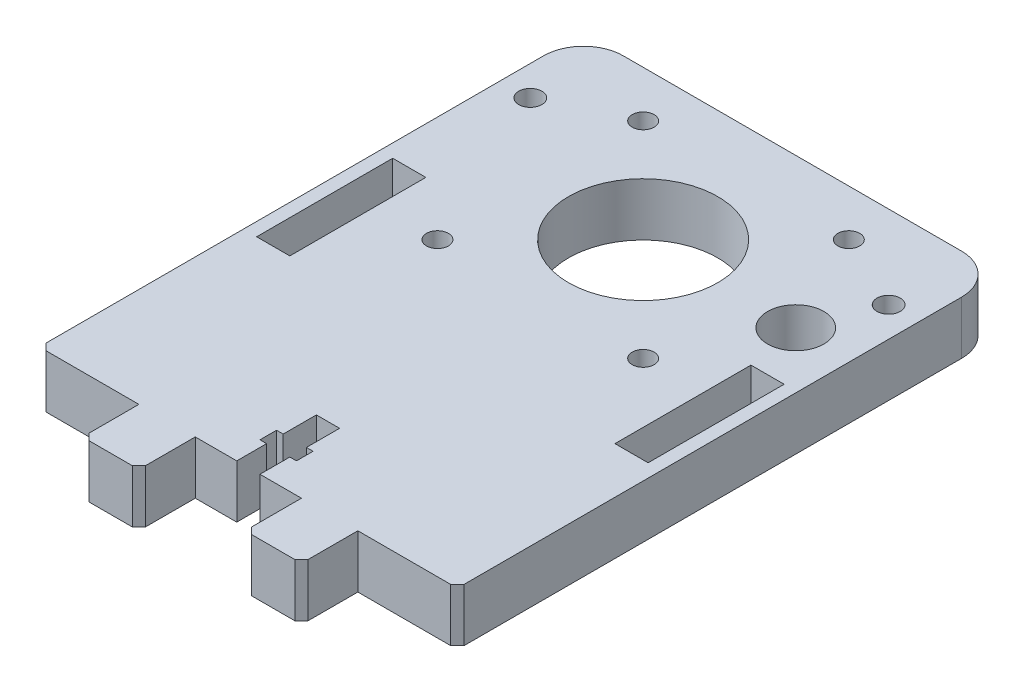
SolidWorks part; units mm, degrees
ref_plane "Front Plane" through (0, 0, 0) normal (0, 0, 1) x (1, 0, 0)
ref_plane "Top Plane" through (0, 0, 0) normal (0, 1, 0) x (1, 0, 0)
ref_plane "Right Plane" through (0, 0, 0) normal (1, 0, 0) x (0, 0, -1)
sketch "Sketch1" plane through (0, 0, 0) normal (0, 1, 0) x (1, 0, 0)
  line L0 (4.8942, 14.4947) -> (4.8942, 89.4947)
  line L1 (10.8942, 95.4947) -> (61.8942, 95.4947)
  line L2 (67.8942, 89.4947) -> (67.8942, 14.4947)
  line L3 (67.8942, 14.4947) -> (66.8942, 13.4947)
  line L4 (66.8942, 13.4947) -> (52.8942, 13.4947)
  line L5 (52.8942, 13.4947) -> (52.8942, 5.9947)
  line L6 (52.8942, 5.9947) -> (51.8942, 4.9947)
  line L7 (51.8942, 4.9947) -> (45.3942, 4.9947)
  line L8 (45.3942, 4.9947) -> (44.3942, 5.9947)
  line L9 (44.3942, 5.9947) -> (44.3942, 13.4947)
  line L10 (44.3942, 13.4947) -> (38.1442, 13.4947)
  line L11 (38.1442, 13.4947) -> (38.1442, 17.9947)
  line L12 (38.1442, 17.9947) -> (39.1442, 17.9947)
  line L13 (39.1442, 17.9947) -> (39.1442, 20.4947)
  line L14 (39.1442, 20.4947) -> (38.1442, 20.4947)
  line L15 (38.1442, 20.4947) -> (38.1442, 25.4947)
  line L16 (38.1442, 25.4947) -> (34.6442, 25.4947)
  line L17 (34.6442, 25.4947) -> (34.6442, 20.4947)
  line L18 (34.6442, 20.4947) -> (33.6442, 20.4947)
  line L19 (33.6442, 20.4947) -> (33.6442, 17.9947)
  line L20 (33.6442, 17.9947) -> (34.6442, 17.9947)
  line L21 (34.6442, 17.9947) -> (34.6442, 13.4947)
  line L22 (34.6442, 13.4947) -> (28.3942, 13.4947)
  line L23 (28.3942, 13.4947) -> (28.3942, 5.9947)
  line L24 (28.3942, 5.9947) -> (27.3942, 4.9947)
  line L25 (27.3942, 4.9947) -> (20.8942, 4.9947)
  line L26 (20.8942, 4.9947) -> (19.8942, 5.9947)
  line L27 (19.8942, 5.9947) -> (19.8942, 13.4947)
  line L28 (19.8942, 13.4947) -> (5.8942, 13.4947)
  line L29 (5.8942, 13.4947) -> (4.8942, 14.4947)
  line L30 (6.8942, 64.7447) -> (11.8942, 64.7447)
  line L31 (11.8942, 64.7447) -> (11.8942, 44.2447)
  line L32 (11.8942, 44.2447) -> (6.8942, 44.2447)
  line L33 (6.8942, 44.2447) -> (6.8942, 64.7447)
  line L34 (65.8942, 64.7447) -> (60.8942, 64.7447)
  line L35 (60.8942, 64.7447) -> (60.8942, 44.2447)
  line L36 (60.8942, 44.2447) -> (65.8942, 44.2447)
  line L37 (65.8942, 44.2447) -> (65.8942, 64.7447)
  line L38 (36.3942, 72.9947) -> (59.3942, 72.9947) construction
  arc A0 (10.8942, 95.4947) -> (4.8942, 89.4947) centre (10.8942, 89.4947) ccw
  arc A1 (67.8942, 89.4947) -> (61.8942, 95.4947) centre (61.8942, 89.4947) ccw
  circle A3 centre (51.8942, 88.4947) radius 1.65
  circle A4 centre (20.8942, 88.4947) radius 1.65
  circle A5 centre (51.8942, 57.4947) radius 1.65
  circle A6 centre (20.8942, 57.4947) radius 1.65
  circle A7 centre (59.3942, 72.9947) radius 4.25
  circle A9 centre (36.3942, 72.9947) radius 11.25
  dimension "D1" = 23
  dimension "D4" = 8.5
  dimension "D2" = 72.9947
  dimension "D3" = 36.3942
extrude "Extrude1" add sketch "Sketch1" along normal blind 8
sketch "Sketch2" plane through (0, 0, -25.4947) normal (0, 0, 1) x (1, 0, 0)
  line L0 (34.6442, 8) -> (38.1442, 0)
  circle A0 centre (36.3942, 4) radius 1
  dimension "D1" = 2
extrude "Extrude2" cut sketch "Sketch2" against normal blind 1 contours A0
sketch "Sketch3" plane through (0, 8, 0) normal (0, 1, 0) x (1, 0, 0)
  line L0 (36.3942, 95.4947) -> (36.3942, 82.9947) construction
  line L1 (61.8942, 95.4947) -> (10.8942, 95.4947) construction
  line L2 (63.3942, 82.9947) -> (9.3942, 82.9947) construction
  circle A0 centre (9.3942, 82.9947) radius 1.75
  circle A1 centre (63.3942, 82.9947) radius 1.75
  dimension "D4" = 3.5
  dimension "D5" = 3.5
  dimension "D1" = 12.5
  dimension "D2" = 27
  dimension "D3" = 54
extrude "Extrude3" cut sketch "Sketch3" against normal blind 10
